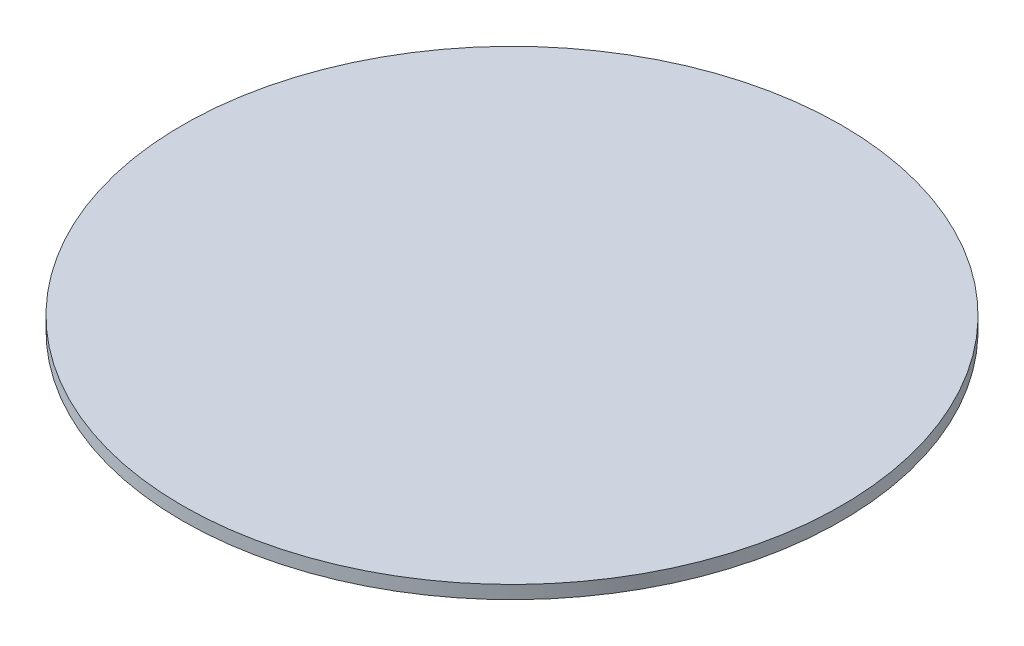
SolidWorks part; units mm, degrees
ref_plane "Front Plane" through (0, 0, 0) normal (0, 0, 1) x (1, 0, 0)
ref_plane "Top Plane" through (0, 0, 0) normal (0, 1, 0) x (1, 0, 0)
ref_plane "Right Plane" through (0, 0, 0) normal (1, 0, 0) x (0, 0, -1)
sketch "Sketch1" plane through (0, 0, 0) normal (0, 1, 0) x (1, 0, 0)
  circle A0 centre (0, 0) radius 300
  dimension "D1" = 600
extrude "Boss-Extrude1" add sketch "Sketch1" along normal blind 12
sketch "Sketch2" plane through (0, 0, 0) normal (0, -1, 0) x (1, 0, 0)
  circle A0 centre (0, 0) radius 280
  circle A1 centre (0, 0) radius 275
  dimension "D1" = 560
  dimension "D2" = 550
extrude "Cut-Extrude1" cut sketch "Sketch2" against normal blind 6
